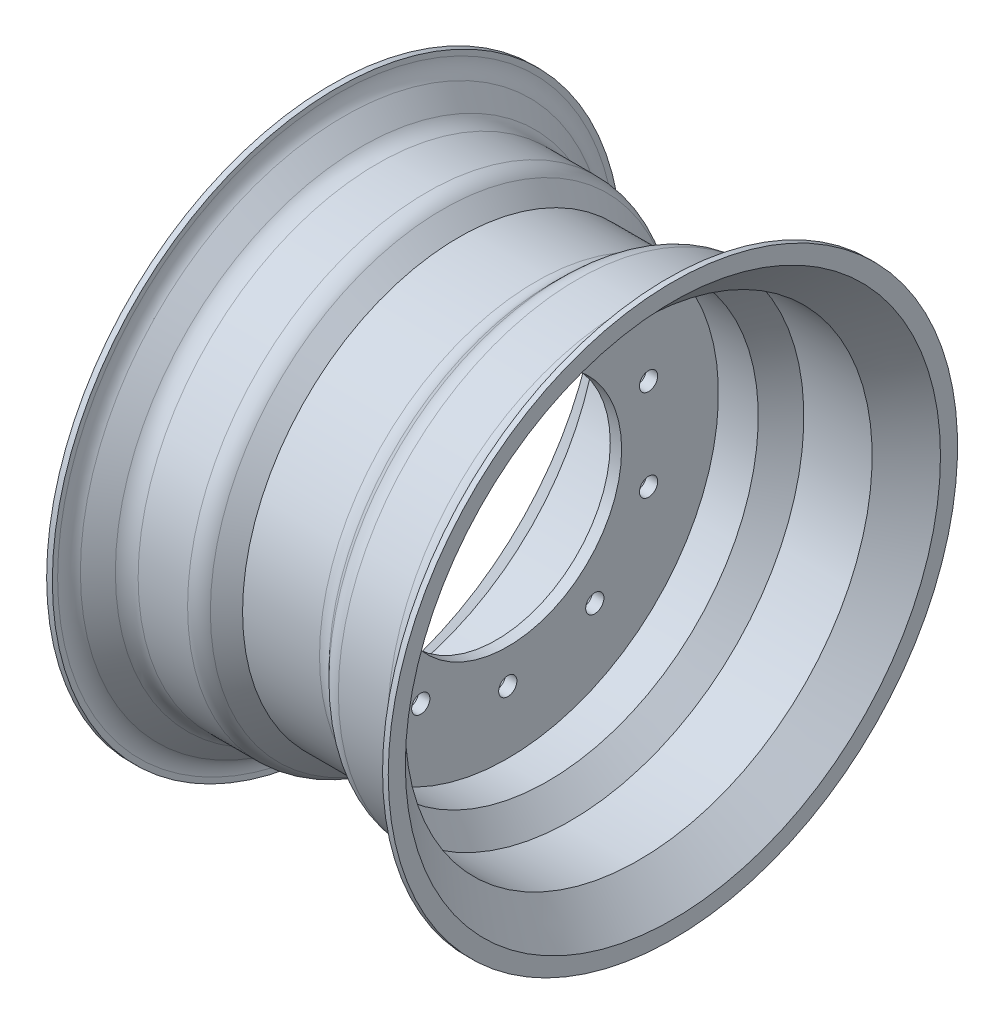
SolidWorks part; units mm, degrees
ref_plane "Front Plane" through (0, 0, 0) normal (0, 0, 1) x (1, 0, 0)
ref_plane "Top Plane" through (0, 0, 0) normal (0, 1, 0) x (1, 0, 0)
ref_plane "Right Plane" through (0, 0, 0) normal (1, 0, 0) x (0, 0, -1)
sketch "Sketch1" plane through (0, 0, 0) normal (0, 0, 1) x (1, 0, 0)
  line L0 (-343.891, 0) -> (0, 0) construction
  line L1 (0, 0) -> (0, 235.0746) construction
  line L2 (-150, 250) -> (-150, 235)
  line L3 (-150, 235) -> (-120, 205)
  line L4 (-120, 205) -> (-60, 205)
  line L5 (-60, 205) -> (-40, 185)
  line L6 (-40, 185) -> (-5, 185)
  line L7 (60, 205) -> (40, 185)
  line L8 (120, 205) -> (60, 205)
  line L9 (150, 235) -> (120, 205)
  line L10 (150, 250) -> (150, 235)
  line L11 (-145, 250) -> (-145, 237.0711)
  line L12 (-145, 237.0711) -> (-117.9289, 210)
  line L13 (-117.9289, 210) -> (-57.9289, 210)
  line L14 (-57.9289, 210) -> (-37.9289, 190)
  line L15 (-37.9289, 190) -> (37.9289, 190)
  line L16 (57.9289, 210) -> (37.9289, 190)
  line L17 (117.9289, 210) -> (57.9289, 210)
  line L18 (145, 237.0711) -> (117.9289, 210)
  line L19 (145, 250) -> (145, 237.0711)
  line L20 (-150, 250) -> (-145, 250)
  line L21 (145, 250) -> (150, 250)
  line L22 (5, 185) -> (40, 185)
  line L24 (-5, 185) -> (-5, 100)
  line L25 (-5, 100) -> (5, 100)
  line L26 (5, 185) -> (5, 100)
  line L27 (-40, 185) -> (40, 185) construction
  point P11 (0, 185)
  dimension "D1" = 250
  dimension "D2" = 15
  dimension "D3" = 30
  dimension "D4" = 60
  dimension "D5" = 20
  dimension "D6" = 40
  dimension "D7" = 135
  dimension "D8" = 135
  dimension "D10" = 10
  dimension "D11" = 5
  dimension "D12" = 100
  dimension "D9" = 5
revolve "Revolve1" add sketch "Sketch1" angle 360 about L0
fillet "Fillet1" radius 20 8 edges at (-145, 0, 237.0711) (-117.9289, 0, 210) (-57.9289, 0, 210) (-40, 0, 185) (37.9289, 0, 190) (57.9289, 0, 210) (117.9289, 0, 210) (145, 0, 237.0711)
sketch "Sketch2" plane through (-5, 0, 0) normal (-1, 0, 0) x (0, 0, 1)
  circle A0 centre (0, 130) radius 8
  dimension "D2" = 16
  dimension "D1" = 130
extrude "Cut-Extrude1" cut sketch "Sketch2" against normal blind 10
pattern_circular "CirPattern1" count 10 over 360 about axis through (0, 0, 0) along (1, 0, 0) of "Cut-Extrude1"
